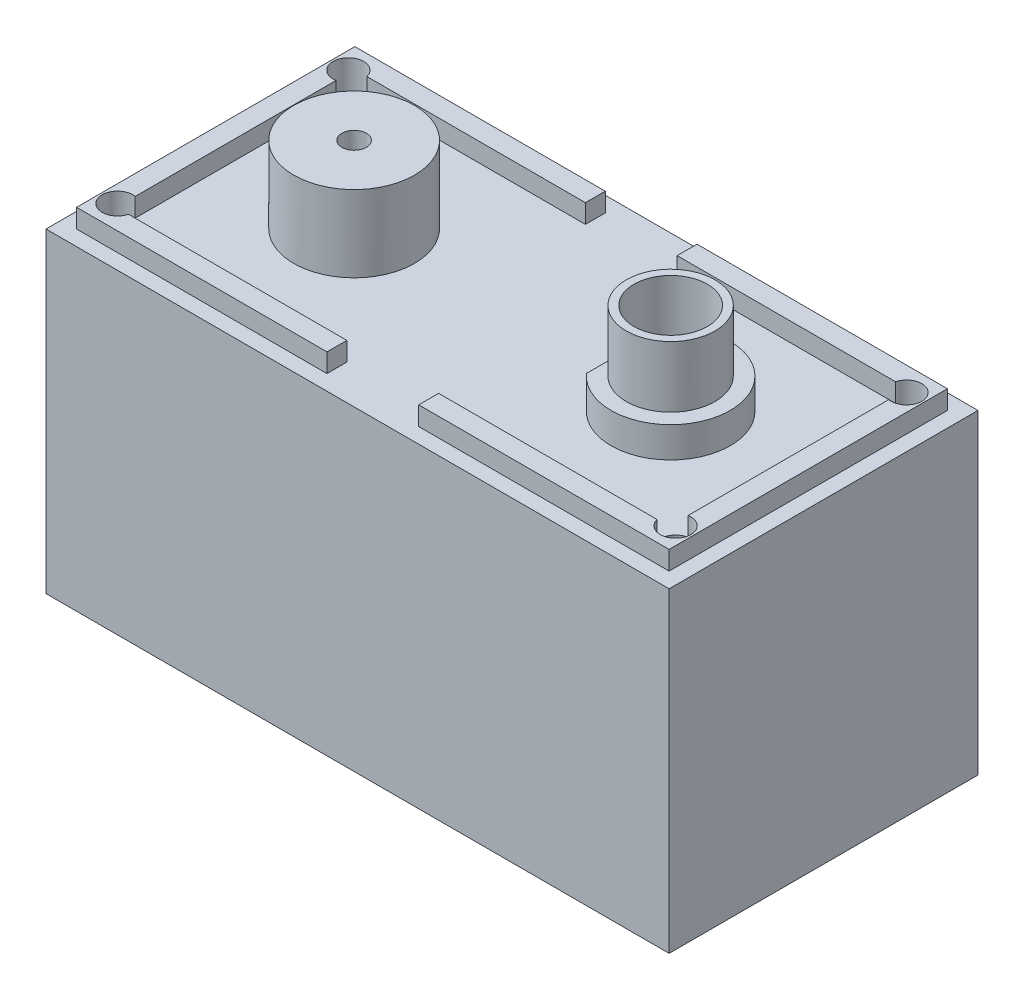
SolidWorks part; units mm, degrees
material "Калифорния"
ref_plane "Спереди" through (0, 0, 0) normal (0, 0, 1) x (1, 0, 0)
ref_plane "Сверху" through (0, 0, 0) normal (0, 1, 0) x (1, 0, 0)
ref_plane "Справа" through (0, 0, 0) normal (1, 0, 0) x (0, 0, -1)
sketch "Эскиз1" plane through (0, 0, 0) normal (0, 1, 0) x (1, 0, 0)
  line L1 (-20.375, -10.1) -> (20.375, -10.1)
  line L2 (-20.375, -10.1) -> (-20.375, 10.1)
  line L3 (-20.375, 10.1) -> (20.375, 10.1)
  line L4 (20.375, -10.1) -> (20.375, 10.1)
  line L5 (-20.375, -10.1) -> (20.375, 10.1) construction
  line L6 (-20.375, 10.1) -> (20.375, -10.1) construction
  point P0 (0, 0)
extrude "Бобышка-Вытянуть1" add sketch "Эскиз1" along normal blind 20.65
shell "Оболочка1" thickness 1.65
sketch "Эскиз2" plane through (0, 20.65, 0) normal (0, 1, 0) x (1, 0, 0)
  line L1 (-20.375, -10.1) -> (20.375, -10.1)
  line L2 (-20.375, -10.1) -> (-20.375, 10.1)
  line L3 (-20.375, 10.1) -> (20.375, 10.1)
  line L4 (20.375, -10.1) -> (20.375, 10.1)
  line L5 (-20.375, -10.1) -> (20.375, 10.1) construction
  line L6 (-20.375, 10.1) -> (20.375, -10.1) construction
  point P0 (0, 0)
extrude "Бобышка-Вытянуть2" add sketch "Эскиз2" against normal blind 1
sketch "Эскиз3" plane through (0, 20.65, 0) normal (0, 1, 0) x (1, 0, 0)
  line L0 (20.375, -10.1) -> (20.375, 10.1) construction
  line L1 (-19.375, -9.1) -> (-3, -9.1)
  line L2 (-19.375, -9.1) -> (-19.375, 9.1)
  line L3 (-19.375, 9.1) -> (-3, 9.1)
  line L4 (19.375, -9.1) -> (19.375, 9.1)
  line L7 (20.375, 10.1) -> (-20.375, 10.1) construction
  line L9 (-18.075, -7.8) -> (-3, -7.8)
  line L10 (-18.075, -7.8) -> (-18.075, 7.8)
  line L11 (-18.075, 7.8) -> (-3, 7.8)
  line L12 (18.075, -7.8) -> (18.075, 7.8)
  line L15 (-3, -7.8) -> (-3, -9.1)
  line L17 (-3, 9.1) -> (-3, 7.8)
  line L19 (3, 9.1) -> (3, 7.8)
  line L22 (3, -7.8) -> (3, -9.1)
  line L24 (3, -9.1) -> (19.375, -9.1)
  line L25 (3, -7.8) -> (18.075, -7.8)
  line L35 (3, 7.8) -> (18.075, 7.8)
  line L36 (3, 9.1) -> (19.375, 9.1)
  point P0 (0, 0)
  point P10 (0, 0)
  dimension "D1" = 1
  dimension "D2" = 1
  dimension "D3" = 1.3
  dimension "D4" = 1.3
extrude "Бобышка-Вытянуть3" add sketch "Эскиз3" along normal blind 1.23
sketch "Эскиз4" plane through (0, 20.65, 0) normal (0, 1, 0) x (1, 0, 0)
  circle A0 centre (-10.325, 0) radius 3.95
  circle A1 centre (-10.325, 0) radius 0.8
extrude "Бобышка-Вытянуть4" add sketch "Эскиз4" along normal blind 5
sketch "Эскиз5" plane through (0, 20.65, 0) normal (0, 1, 0) x (1, 0, 0)
  line L2 (7.475, 2.6077) -> (7.475, -2.6077)
  arc A0 (7.475, -2.6077) -> (7.475, 2.6077) centre (10.375, 0) ccw
extrude "Бобышка-Вытянуть5" add sketch "Эскиз5" along normal blind 2
sketch "Эскиз6" plane through (0, 22.65, 0) normal (0, 1, 0) x (1, 0, 0)
  circle A0 centre (10.375, 0) radius 2.9
  circle A1 centre (10.375, 0) radius 2.4
extrude "Бобышка-Вытянуть6" add sketch "Эскиз6" along normal blind 4
sketch "Эскиз7" plane through (0, 0, 0) normal (0, -1, 0) x (1, 0, 0)
  line L0 (20.375, 10.1) -> (20.375, -10.1) construction
  line L1 (-19.475, -9.2) -> (19.475, -9.2)
  line L2 (-19.475, -9.2) -> (-19.475, 9.2)
  line L3 (-19.475, 9.2) -> (19.475, 9.2)
  line L4 (19.475, -9.2) -> (19.475, 9.2)
  line L5 (-19.475, -9.2) -> (19.475, 9.2) construction
  line L6 (-19.475, 9.2) -> (19.475, -9.2) construction
  line L7 (-20.375, 10.1) -> (20.375, 10.1) construction
  point P0 (0, 0)
  dimension "D1" = 0.9
  dimension "D2" = 0.9
extrude "Вырез-Вытянуть2" cut sketch "Эскиз7" against normal blind 2.6
sketch "Эскиз9" plane through (0, 19.65, 0) normal (0, -1, 0) x (1, 0, 0)
  circle A0 centre (-18.25, 7.55) radius 1.4
  circle A1 centre (-18.25, -7.55) radius 1.4
  circle A2 centre (18.25, -7.55) radius 1.4
  circle A3 centre (18.25, 7.55) radius 1.4
extrude "Бобышка-Вытянуть7" add sketch "Эскиз9" along normal up to vertex
sketch "Эскиз8" plane through (0, 21.88, 0) normal (0, 1, 0) x (1, 0, 0)
  line L0 (-17.25, 7.55) -> (17.25, 7.55) construction
  line L1 (-17.25, -7.55) -> (17.25, -7.55) construction
  line L2 (18.25, 6.55) -> (18.25, -6.55) construction
  line L3 (-18.25, 6.55) -> (-18.25, -6.55) construction
  line L4 (-18.25, 7.55) -> (18.25, -7.55) construction
  line L5 (-18.25, -7.55) -> (18.25, 7.55) construction
  circle A0 centre (-18.25, 7.55) radius 1
  circle A1 centre (18.25, 7.55) radius 1
  circle A2 centre (18.25, -7.55) radius 1
  circle A3 centre (-18.25, -7.55) radius 1
  point P14 (0, 0)
  dimension "D1" = 13.1
  dimension "D2" = 34.5
extrude "Вырез-Вытянуть3" cut sketch "Эскиз8" against normal up to vertex
